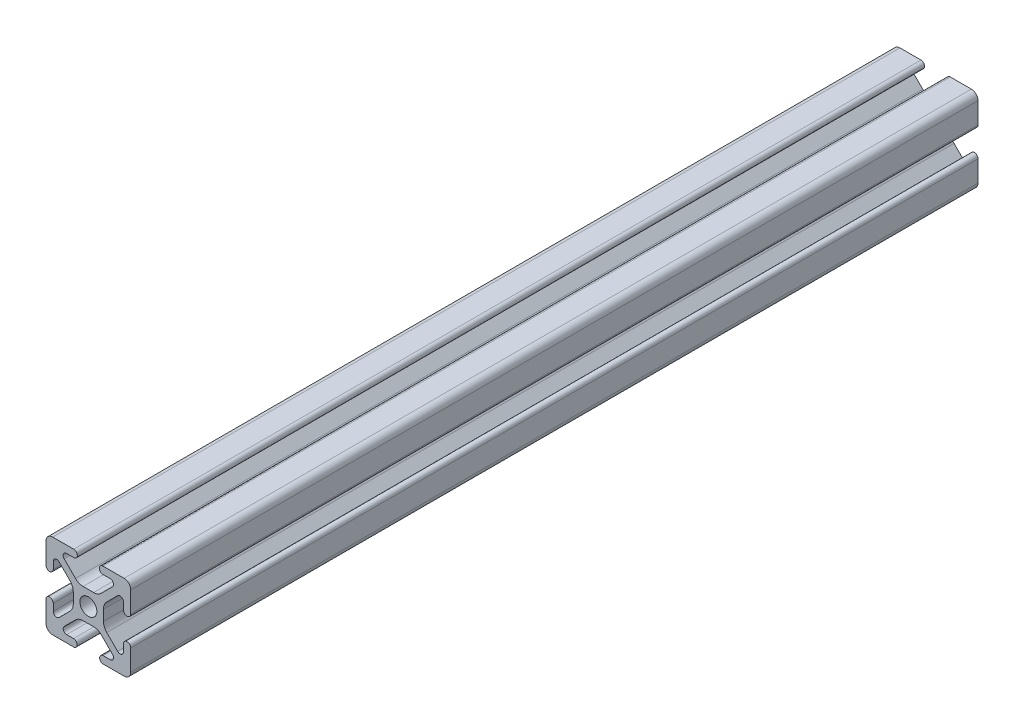
SolidWorks part; units mm, degrees
material "6005A-T61"
ref_plane "Front Plane" through (0, 0, 0) normal (0, 0, 1) x (1, 0, 0)
ref_plane "Top Plane" through (0, 0, 0) normal (0, 1, 0) x (1, 0, 0)
ref_plane "Right Plane" through (0, 0, 0) normal (1, 0, 0) x (0, 0, -1)
sketch "Sketch1" plane through (0, 0, 0) normal (0, 0, 1) x (1, 0, 0)
  line L0 (-8.6363, 7.1116) -> (-5.4322, 3.9121)
  line L1 (-4.455, 1.5554) -> (-4.455, -1.5554)
  line L2 (-5.4322, -3.9121) -> (-8.6363, -7.1116)
  line L3 (-10.36, -6.3969) -> (-10.36, -4.32)
  line L4 (-12.5, -4.32) -> (-12.5, -8.6518)
  line L5 (-12.5, -8.6518) -> (-12.5, -10.5371)
  line L6 (-10.5371, -12.5) -> (-8.4416, -12.5)
  line L7 (-8.4416, -12.5) -> (-4.3879, -12.5)
  line L8 (-4.3879, -10.36) -> (-6.42, -10.36)
  line L9 (-7.1337, -8.6353) -> (-3.7953, -5.3018)
  line L10 (-1.5554, -4.375) -> (1.5554, -4.375)
  line L11 (10.36, 4.32) -> (10.36, 6.3969)
  line L12 (12.5, 7.9913) -> (12.5, 4.32)
  line L13 (12.5, 10.5371) -> (12.5, 7.9913)
  line L14 (4.32, 12.5) -> (10.5371, 12.5)
  line L16 (6.42, 10.36) -> (4.32, 10.36)
  line L17 (3.7953, 5.3018) -> (7.1337, 8.6353)
  line L18 (7.1337, -8.6353) -> (3.7953, -5.3018)
  line L19 (4.3879, -10.36) -> (6.42, -10.36)
  line L20 (8.4416, -12.5) -> (4.3879, -12.5)
  line L21 (10.5371, -12.5) -> (8.4416, -12.5)
  line L22 (12.5, -8.6518) -> (12.5, -10.5371)
  line L23 (12.5, -4.32) -> (12.5, -8.6518)
  line L24 (10.36, -6.3969) -> (10.36, -4.32)
  line L25 (5.4322, -3.9121) -> (8.6363, -7.1116)
  line L26 (4.455, 1.5554) -> (4.455, -1.5554)
  line L27 (8.6363, 7.1116) -> (5.4322, 3.9121)
  line L28 (1.5554, 4.375) -> (-1.5554, 4.375)
  line L29 (-3.7953, 5.3018) -> (-7.1337, 8.6353)
  line L30 (-6.42, 10.36) -> (-4.32, 10.36)
  line L32 (-4.32, 12.5) -> (-10.5371, 12.5)
  line L33 (-12.5, 10.5371) -> (-12.5, 7.9913)
  line L34 (-12.5, 7.9913) -> (-12.5, 4.32)
  line L35 (-10.36, 4.32) -> (-10.36, 6.3969)
  line L36 (-15.7693, 0) -> (12.5, 0) construction
  line L37 (0, 13.9334) -> (0, -12.3541) construction
  circle A0 centre (0, 0) radius 2.5
  arc A1 (-8.6363, 7.1116) -> (-10.36, 6.3969) centre (-9.35, 6.3969) ccw
  arc A2 (-4.455, 1.5554) -> (-5.4322, 3.9121) centre (-7.7855, 1.5554) ccw
  arc A3 (-5.4322, -3.9121) -> (-4.455, -1.5554) centre (-7.7855, -1.5554) ccw
  arc A4 (-10.36, -6.3969) -> (-8.6363, -7.1116) centre (-9.35, -6.3969) ccw
  arc A5 (-10.36, -4.32) -> (-12.5, -4.32) centre (-11.43, -4.32) ccw
  arc A6 (-12.5, -10.5371) -> (-10.5371, -12.5) centre (-10.5371, -10.5371) ccw
  arc A7 (-4.3879, -12.5) -> (-4.3879, -10.36) centre (-4.3879, -11.43) ccw
  arc A8 (-7.1337, -8.6353) -> (-6.42, -10.36) centre (-6.42, -9.35) ccw
  arc A9 (-1.5554, -4.375) -> (-3.7953, -5.3018) centre (-1.5554, -7.545) ccw
  arc A10 (12.5, 4.32) -> (10.36, 4.32) centre (11.43, 4.32) cw
  arc A11 (10.5371, 12.5) -> (12.5, 10.5371) centre (10.5371, 10.5371) cw
  arc A12 (4.32, 10.36) -> (4.32, 12.5) centre (4.32, 11.43) cw
  arc A13 (6.42, 10.36) -> (7.1337, 8.6353) centre (6.42, 9.35) cw
  arc A14 (3.7953, 5.3018) -> (1.5554, 4.375) centre (1.5554, 7.545) cw
  arc A15 (1.5554, -4.375) -> (3.7953, -5.3018) centre (1.5554, -7.545) cw
  arc A16 (7.1337, -8.6353) -> (6.42, -10.36) centre (6.42, -9.35) cw
  arc A17 (4.3879, -12.5) -> (4.3879, -10.36) centre (4.3879, -11.43) cw
  arc A18 (12.5, -10.5371) -> (10.5371, -12.5) centre (10.5371, -10.5371) cw
  arc A19 (10.36, -4.32) -> (12.5, -4.32) centre (11.43, -4.32) cw
  arc A20 (10.36, -6.3969) -> (8.6363, -7.1116) centre (9.35, -6.3969) cw
  arc A21 (5.4322, -3.9121) -> (4.455, -1.5554) centre (7.7855, -1.5554) cw
  arc A22 (4.455, 1.5554) -> (5.4322, 3.9121) centre (7.7855, 1.5554) cw
  arc A23 (8.6363, 7.1116) -> (10.36, 6.3969) centre (9.35, 6.3969) cw
  arc A24 (-3.7953, 5.3018) -> (-1.5554, 4.375) centre (-1.5554, 7.545) ccw
  arc A25 (-6.42, 10.36) -> (-7.1337, 8.6353) centre (-6.42, 9.35) ccw
  arc A26 (-4.32, 10.36) -> (-4.32, 12.5) centre (-4.32, 11.43) ccw
  arc A27 (-10.5371, 12.5) -> (-12.5, 10.5371) centre (-10.5371, 10.5371) ccw
  arc A28 (-12.5, 4.32) -> (-10.36, 4.32) centre (-11.43, 4.32) ccw
  dimension "D4" = 14.86
  dimension "D5" = 2.14
  dimension "D6" = 6.5
  dimension "D7" = 8.75
  dimension "D8" = 1.01
  dimension "D9" = 3.17
  dimension "D14" = 5
  dimension "D1" = 25
  dimension "D2" = 8.91
  dimension "D3" = 12.5
  dimension "D12" = 2.14
extrude "Extrude1" add sketch "Sketch1" against normal blind 250
sketch "Sketch3" plane through (4.455, 0, 0) normal (1, 0, 0) x (0, 0, -1)
  circle A0 centre (19.4459, 0) radius 1.0294
extrude "Cut-Extrude1" cut sketch "Sketch3" against normal through all
